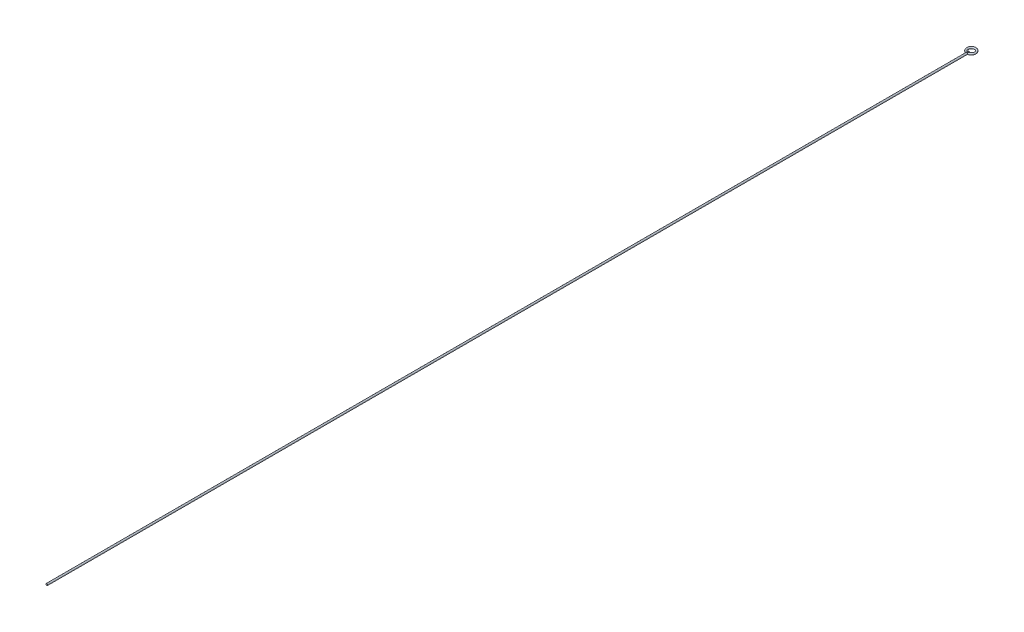
SolidWorks part; units mm, degrees
material "AISI 1010 Steel, hot rolled bar"
ref_plane "Front Plane" through (0, 0, 0) normal (0, 0, 1) x (1, 0, 0)
ref_plane "Top Plane" through (0, 0, 0) normal (0, 1, 0) x (1, 0, 0)
ref_plane "Right Plane" through (0, 0, 0) normal (1, 0, 0) x (0, 0, -1)
sketch "Sketch1" plane through (0, 0, 0) normal (0, 0, 1) x (1, 0, 0)
  circle A0 centre (0, 0) radius 2
  dimension "D1" = 4
extrude "Boss-Extrude1" add sketch "Sketch1" along normal blind 2150 from offset 6
sketch "Sketch4" plane through (0, 0, 0) normal (0, 0, -1) x (-1, 0, 0)
  line L0 (0, 3.776) -> (0, -3.776)
  circle A0 centre (-9, 0) radius 2
  point P4 (0, 0)
  dimension "D1" = 9
revolve "Revolve1" add sketch "Sketch4" angle 360 about L0
sketch "Sketch7" plane through (0, 0, 0) normal (0, 1, 0) x (1, 0, 0)
  circle A0 centre (0, -9) radius 2
  dimension "D1" = 4
  dimension "D2" = 9
extrude "Boss-Extrude2" add sketch "Sketch7" along normal blind 2.1
sketch "Sketch8" plane through (0, 0, 0) normal (0, 1, 0) x (1, 0, 0)
  line L0 (0, 0) -> (0, -1800) construction
  dimension "D1" = 1800
